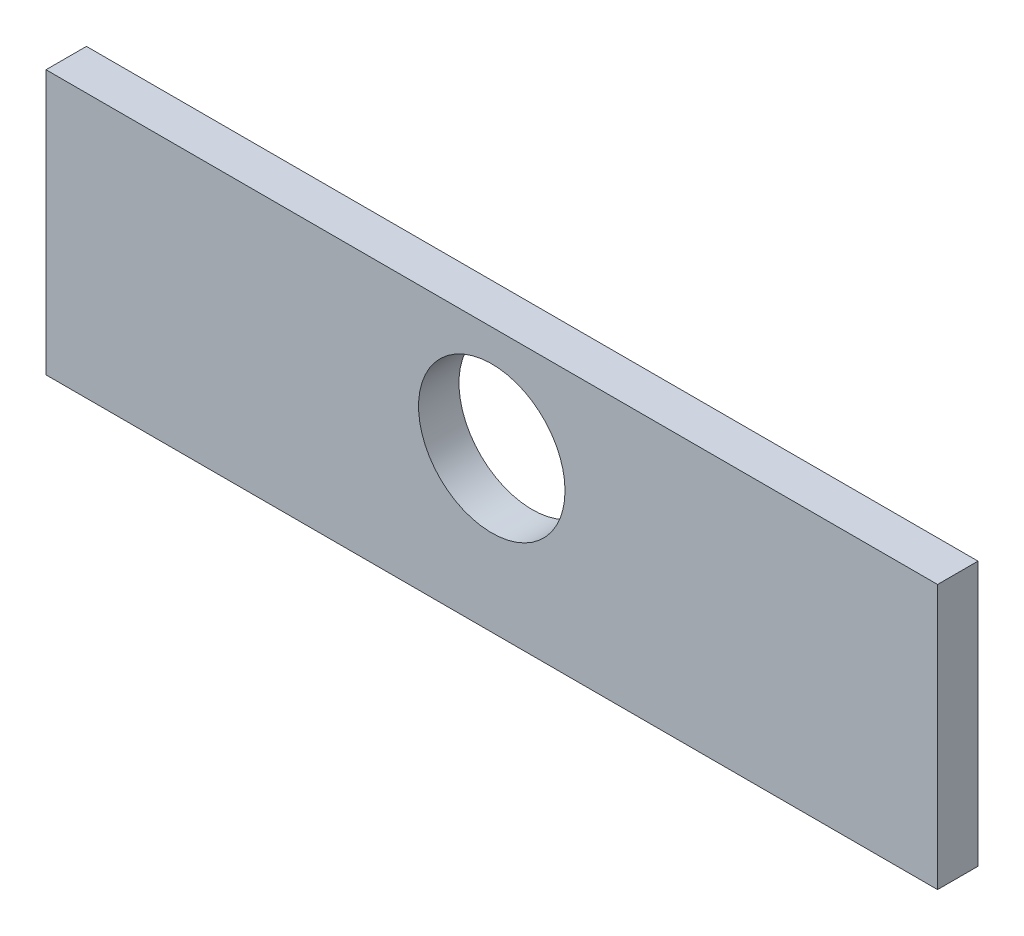
SolidWorks part; units mm, degrees
ref_plane "Front Plane" through (0, 0, 0) normal (0, 0, 1) x (1, 0, 0)
ref_plane "Top Plane" through (0, 0, 0) normal (0, 1, 0) x (1, 0, 0)
ref_plane "Right Plane" through (0, 0, 0) normal (1, 0, 0) x (0, 0, -1)
sketch "Sketch1" plane through (0, 0, 0) normal (0, 0, 1) x (1, 0, 0)
  line L1 (-70, 20.75) -> (70, 20.75)
  line L2 (-70, 20.75) -> (-70, -20.75)
  line L3 (-70, -20.75) -> (70, -20.75)
  line L4 (70, 20.75) -> (70, -20.75)
  line L5 (-70, 20.75) -> (70, -20.75) construction
  line L6 (-70, -20.75) -> (70, 20.75) construction
  point P0 (0, 0)
  dimension "D1" = 41.5
  dimension "D2" = 140
extrude "Boss-Extrude1" add sketch "Sketch1" along normal blind 6.35
sketch "Sketch2" plane through (0, 0, 6.35) normal (0, 0, 1) x (1, 0, 0)
  line L0 (-70, -20.75) -> (70, -20.75) construction
  circle A0 centre (0, 4.25) radius 11.5
  dimension "D1" = 23
  dimension "D2" = 25
extrude "Cut-Extrude1" cut sketch "Sketch2" against normal through all
